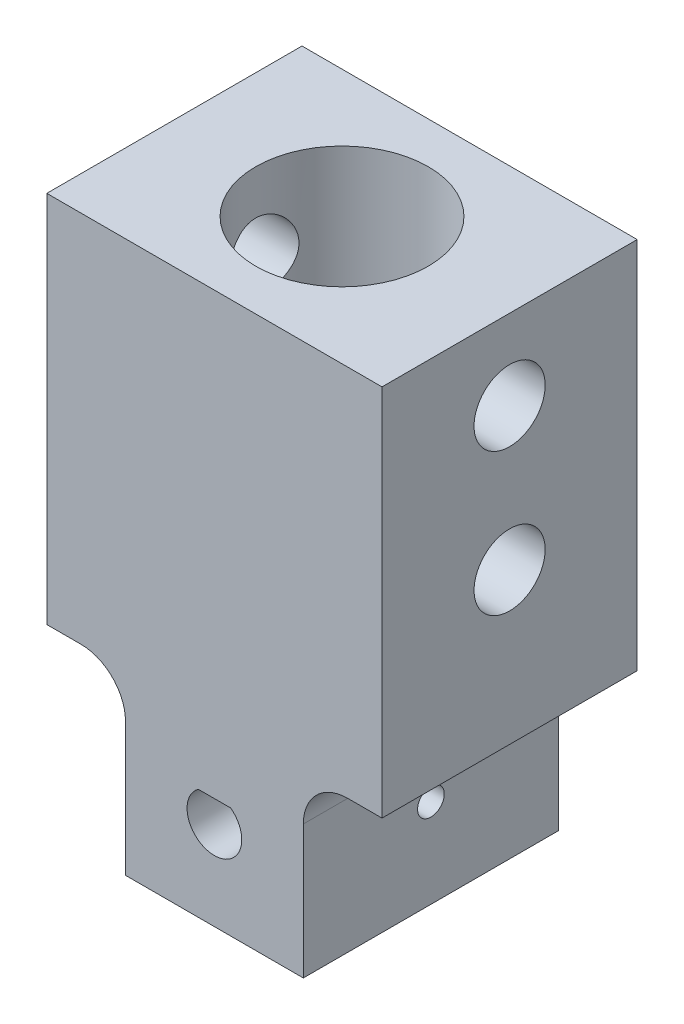
SolidWorks part; units mm, degrees
material "Plain Carbon Steel"
ref_plane "Front" through (0, 0, 0) normal (0, 0, 1) x (1, 0, 0)
ref_plane "Top" through (0, 0, 0) normal (0, 1, 0) x (1, 0, 0)
ref_plane "Right" through (0, 0, 0) normal (1, 0, 0) x (0, 0, -1)
sketch "Sketch11" plane through (0, 0, 0) normal (0, 1, 0) x (1, 0, 0)
  line L1 (-18.85, 14.35) -> (18.85, 14.35)
  line L2 (-18.85, 14.35) -> (-18.85, -14.35)
  line L3 (-18.85, -14.35) -> (18.85, -14.35)
  line L4 (18.85, 14.35) -> (18.85, -14.35)
  line L5 (-18.85, 14.35) -> (18.85, -14.35) construction
  line L6 (-18.85, -14.35) -> (18.85, 14.35) construction
  circle A0 centre (0, 0) radius 9.7
  point P0 (0, 0)
  dimension "D3" = 19.4
  dimension "D1" = 37.7
  dimension "D2" = 28.7
extrude "Boss-Extrude1" add sketch "Sketch11" along normal blind 42
sketch "Sketch15" plane through (0, 0, 14.35) normal (0, 0, 1) x (1, 0, 0)
  line L0 (18.85, 42) -> (18.85, 0) construction
  line L1 (-18.85, 0) -> (18.85, 0)
  line L2 (-18.85, 0) -> (-18.85, 5)
  line L3 (-18.85, 5) -> (18.85, 5)
  line L4 (18.85, 0) -> (18.85, 5)
  dimension "D1" = 5
extrude "Boss-Extrude3" add sketch "Sketch15" against normal up to surface (28.7 mm away) up to face at (0, 21, -14.35)
sketch "Sketch12" plane through (18.85, 0, 0) normal (1, 0, 0) x (0, 0, -1)
  line L0 (-22.564, 25) -> (28.4467, 25) construction
  circle A0 centre (0, 33) radius 4
  circle A1 centre (0, 17) radius 4
  dimension "D1" = 25
  dimension "D2" = 8
  dimension "D3" = 8
extrude "Cut-Extrude1" cut sketch "Sketch12" against normal blind 40
sketch "Sketch23" plane through (0, 0, 0) normal (0, 0, 1) x (1, 0, 0)
  line L0 (0, -10) -> (0, -13.075) construction
  line L1 (-10, 0) -> (10, 0)
  line L2 (-10, 0) -> (-10, -20)
  line L3 (-10, -20) -> (10, -20)
  line L4 (10, 0) -> (10, -20)
  line L5 (-10, 0) -> (10, -20) construction
  line L6 (-10, -20) -> (10, 0) construction
  line L7 (-1.8248, -7.525) -> (1.8248, -7.525)
  circle A0 centre (0, -10) radius 3.075
  point P0 (0, -10)
  point P11 (0, -12.1357)
  dimension "D3" = 6.15
  dimension "D1" = 10
  dimension "D4" = 5.55
extrude "Boss-Extrude4" add sketch "Sketch23" against normal mid plane 28.7 contours L4 L1 L2 L3 A0 | L7 A0
sketch "Sketch24" plane through (0, 0, 0) normal (1, 0, 0) x (0, 0, -1)
  circle A0 centre (0, -10) radius 1.5
  point P2 (0, 0)
  point P4 (0, -8.1243)
  dimension "D1" = 3
  dimension "D2" = 10
extrude "Cut-Extrude2" cut sketch "Sketch24" against normal through all both and the other way through all
fillet "Fillet1" radius 5 2 edges at (-10, 0, 0) (10, 0, 0)
